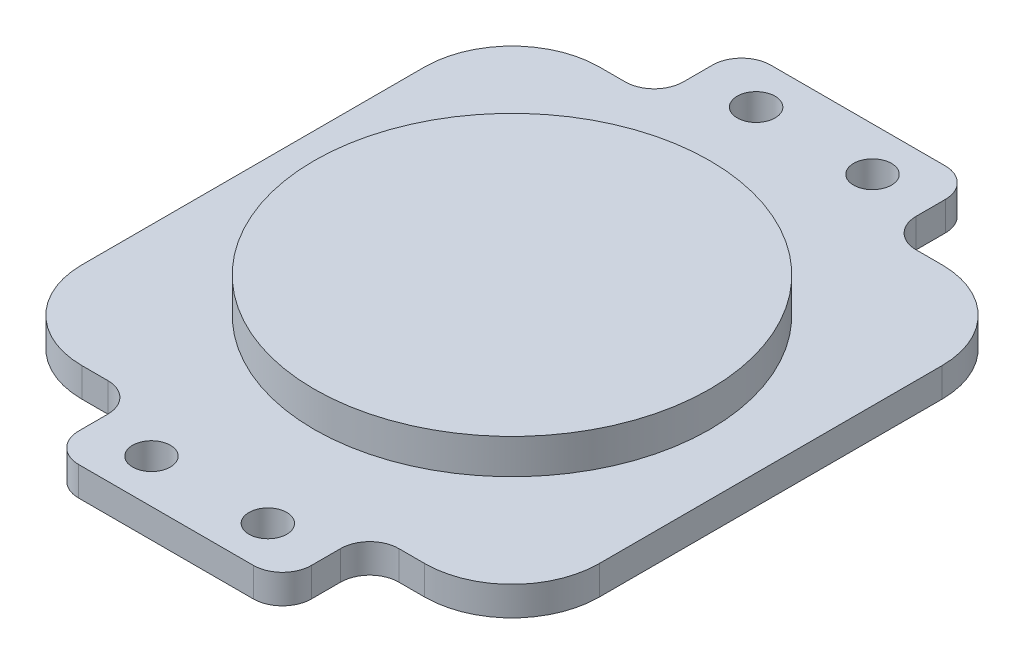
SolidWorks part; units mm, degrees
ref_plane "Front Plane" through (0, 0, 0) normal (0, 0, 1) x (1, 0, 0)
ref_plane "Top Plane" through (0, 0, 0) normal (0, 1, 0) x (1, 0, 0)
ref_plane "Right Plane" through (0, 0, 0) normal (1, 0, 0) x (0, 0, -1)
sketch "Sketch1" plane through (0, 0, 0) normal (0, 1, 0) x (1, 0, 0)
  line L1 (-44.45, -44.45) -> (44.45, -44.45)
  line L2 (-44.45, -44.45) -> (-44.45, 44.45)
  line L3 (-44.45, 44.45) -> (44.45, 44.45)
  line L4 (44.45, -44.45) -> (44.45, 44.45)
  line L5 (-44.45, -44.45) -> (44.45, 44.45) construction
  line L6 (-44.45, 44.45) -> (44.45, -44.45) construction
  point P0 (0, 0)
  dimension "D1" = 88.9
  dimension "D2" = 88.9
extrude "Boss-Extrude1" add sketch "Sketch1" along normal blind 5
sketch "Sketch2" plane through (0, 5, 0) normal (0, 1, 0) x (1, 0, 0)
  circle A0 centre (0, 0) radius 34
extrude "Boss-Extrude2" add sketch "Sketch2" along normal blind 6
sketch "Sketch3" plane through (0, 0, 0) normal (0, -1, 0) x (1, 0, 0)
  line L0 (-44.45, 44.45) -> (44.45, 44.45) construction
  line L1 (0, 44.45) -> (20, 44.45)
  line L2 (0, 44.45) -> (0, 59.45)
  line L3 (0, 59.45) -> (20, 59.45)
  line L4 (20, 44.45) -> (20, 59.45)
  line L5 (44.45, -44.45) -> (-44.45, -44.45) construction
  line L6 (0, 44.45) -> (-20, 44.45)
  line L7 (0, 44.45) -> (0, 59.45)
  line L8 (0, 59.45) -> (-20, 59.45)
  line L9 (-20, 44.45) -> (-20, 59.45)
  line L10 (0, -44.45) -> (20, -44.45)
  line L11 (0, -44.45) -> (0, -59.45)
  line L12 (0, -59.45) -> (20, -59.45)
  line L13 (20, -44.45) -> (20, -59.45)
  line L15 (0, -44.45) -> (-20, -44.45)
  line L16 (0, -44.45) -> (0, -59.45)
  line L17 (0, -59.45) -> (-20, -59.45)
  line L18 (-20, -44.45) -> (-20, -59.45)
  line M9 (44.45, 44.45) -> (-44.45, 44.45)
  line M11 (-44.45, -44.45) -> (44.45, -44.45)
  dimension "D1" = 15
  dimension "D2" = 20
  dimension "D3" = 20
  dimension "D4" = 15
  dimension "D5" = 15
  dimension "D6" = 20
  dimension "D7" = 20
extrude "Boss-Extrude3" add sketch "Sketch3" against normal blind 5 contours L9 L2 L8 M9 | L4 L3 L2 M9 | L13 L11 L12 M11 | L18 L17 L11 M11
sketch "Sketch4" plane through (0, 0, 0) normal (0, -1, 0) x (1, 0, 0)
  line L0 (-20, 44.45) -> (-20, 59.45) construction
  line L1 (20, 44.45) -> (20, 59.45) construction
  line L2 (20, 59.45) -> (-20, 59.45) construction
  circle A0 centre (10, 51.95) radius 3.25
  circle A1 centre (-10, 51.95) radius 3.25
  circle A2 centre (10, -51.95) radius 3.25
  circle A3 centre (-10, -51.95) radius 3.25
  dimension "D1" = 10
  dimension "D2" = 10
  dimension "D3" = 7.5
  dimension "D4" = 7.5
extrude "Cut-Extrude1" cut sketch "Sketch4" against normal blind 5
fillet "Fillet1" radius 15 4 edges at (-44.45, 2.5, 44.45) (44.45, 2.5, 44.45) (44.45, 2.5, -44.45) (-44.45, 2.5, -44.45)
fillet "Fillet2" radius 5 8 edges at (20, 2.5, -44.45) (20, 2.5, -59.45) (-20, 2.5, -59.45) (-20, 2.5, -44.45) (-20, 2.5, 44.45) (20, 2.5, 44.45) (-20, 2.5, 59.45) (20, 2.5, 59.45)
